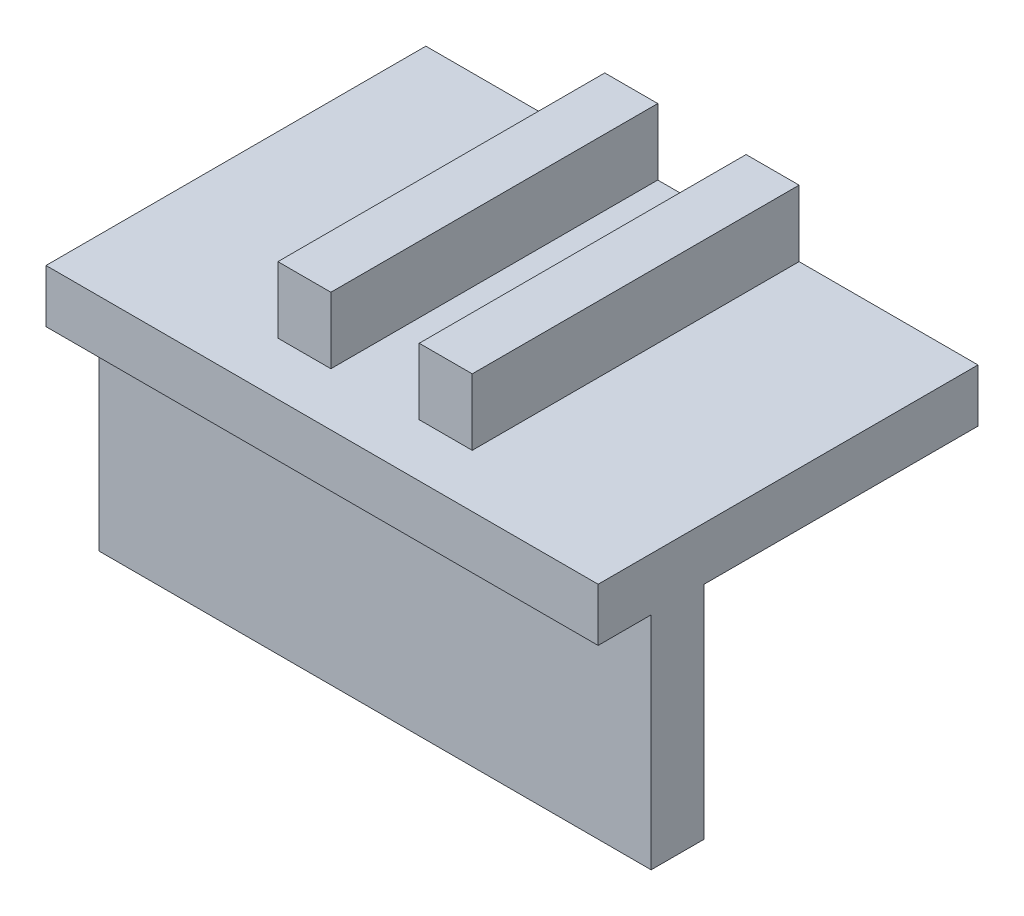
SolidWorks part; units mm, degrees
ref_plane "Front Plane" through (0, 0, 0) normal (0, 0, 1) x (1, 0, 0)
ref_plane "Top Plane" through (0, 0, 0) normal (0, 1, 0) x (1, 0, 0)
ref_plane "Right Plane" through (0, 0, 0) normal (1, 0, 0) x (0, 0, -1)
sketch "Sketch1" plane through (0, 0, 0) normal (0, 0, 1) x (1, 0, 0)
  line L1 (0, 0) -> (125, 0)
  line L2 (0, 0) -> (0, 62)
  line L3 (0, 62) -> (125, 62)
  line L4 (125, 0) -> (125, 62)
  dimension "D1" = 125
  dimension "D2" = 62
extrude "Boss-Extrude2" add sketch "Sketch1" along normal blind 12
sketch "Sketch3" plane through (0, 62, 0) normal (0, 1, 0) x (1, 0, 0)
  line L5 (0, 0) -> (125, 0)
  line L6 (0, 0) -> (0, 62)
  line L7 (0, 62) -> (125, 62)
  line L8 (125, 0) -> (125, 62)
  dimension "D1" = 62
  dimension "D2" = 125
extrude "Boss-Extrude3" add sketch "Sketch3" against normal blind 12
sketch "Sketch4" plane through (0, 62, 0) normal (0, 1, 0) x (1, 0, 0)
  line L0 (40.5, 62) -> (40.5, -12)
  line L1 (125, -12) -> (125, 62) construction
  line L2 (0, -12) -> (0, 62) construction
  line L3 (72.5, 62) -> (72.5, -12)
  line L4 (125, 62) -> (0, 62) construction
  line L5 (125, -12) -> (0, -12) construction
  line L6 (52.5, 62) -> (52.5, -12)
  line L7 (40.5, -12) -> (52.5, -12)
  line L8 (84.5, 62) -> (84.5, -12)
  line L9 (40.5, 62) -> (52.5, 62)
  line L10 (72.5, 62) -> (84.5, 62)
  line L11 (72.5, -12) -> (84.5, -12)
  point P14 (40.5, 25)
  dimension "D1" = 40.5
  dimension "D2" = 40.5
  dimension "D3" = 12
  dimension "D4" = 12
  dimension "D5" = 20
extrude "Boss-Extrude4" add sketch "Sketch4" along normal blind 15 contours L7 L6 L9 L0 | L11 L8 L10 L3
sketch "Sketch5" plane through (0, 0, 12) normal (0, 0, 1) x (1, 0, 0)
  line L0 (0, 62) -> (0, 50)
  line L1 (0, 62) -> (0, 0) construction
  line L2 (0, 50) -> (125, 50)
  line L4 (125, 0) -> (125, 62) construction
  line L5 (125, 50) -> (125, 62)
  line L6 (125, 62) -> (0, 62)
  dimension "D1" = 12
extrude "Boss-Extrude5" add sketch "Sketch5" along normal blind 12
ref_plane "Plane1" through (0, 56, 0) normal (0, 1, 0) x (1, 0, 0)
